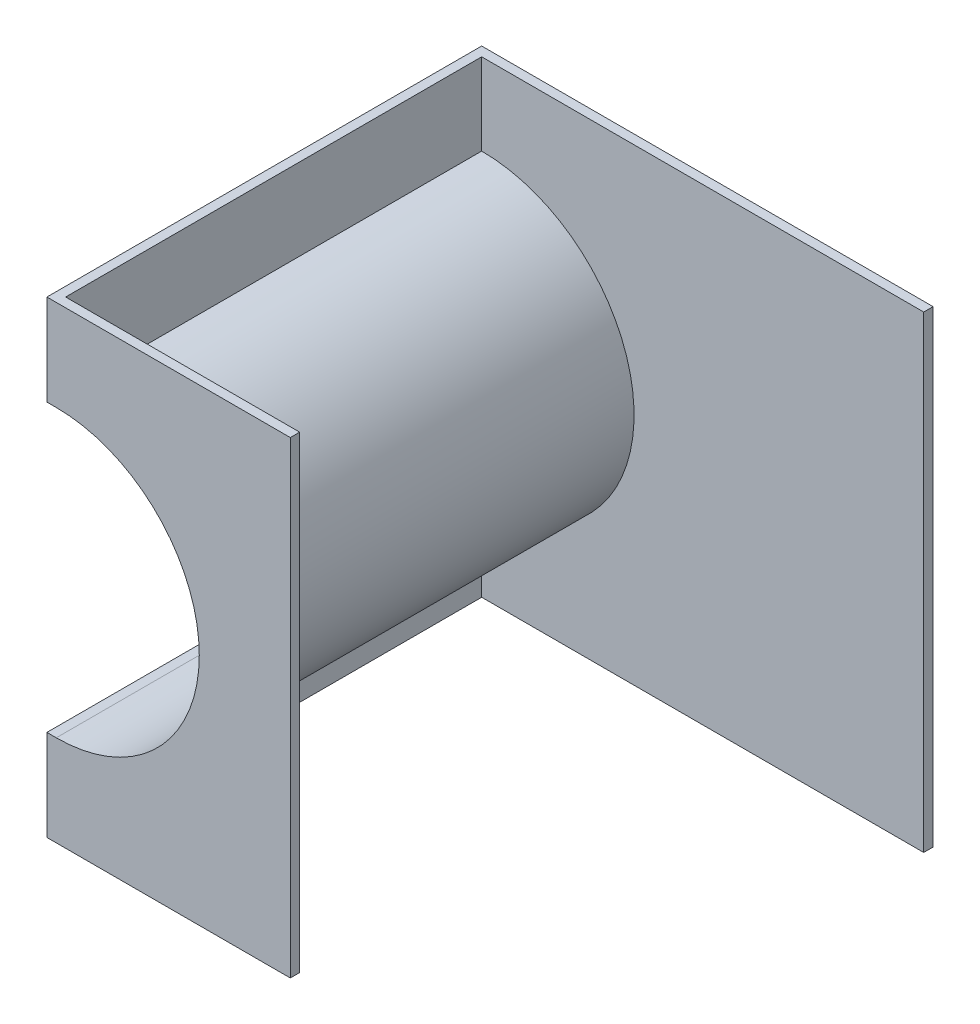
SolidWorks part; units mm, degrees
ref_plane "Přední rovina" through (0, 0, 0) normal (0, 0, 1) x (1, 0, 0)
ref_plane "Horní rovina" through (0, 0, 0) normal (0, 1, 0) x (1, 0, 0)
ref_plane "Pravá rovina" through (0, 0, 0) normal (1, 0, 0) x (0, 0, -1)
sketch "Skica1" plane through (0, 0, 0) normal (0, 0, 1) x (1, 0, 0)
  line L6 (0, 0) -> (0, 0.293) construction
  line L7 (0, 0) -> (0, -0.293) construction
  line L8 (0, 0.275) -> (-0.018, 0.275)
  line L9 (-0.018, 0.275) -> (-0.018, 0.45)
  line L10 (-0.018, 0.45) -> (0, 0.45)
  line L11 (0, 0.45) -> (0, 0.293)
  line L12 (0, -0.275) -> (-0.018, -0.275)
  line L13 (-0.018, -0.275) -> (-0.018, -0.45)
  line L14 (-0.018, -0.45) -> (0, -0.45)
  line L15 (0, -0.45) -> (0, -0.293)
  line L16 (0.275, 0) -> (0.293, 0) construction
  arc A2 (0, -0.293) -> (0, 0.293) centre (0, 0) ccw
  arc A3 (0, 0.275) -> (0, -0.275) centre (0, 0) cw
  dimension "D4" = 0.293
  dimension "D2" = 0.018
  dimension "D3" = 0.9
  dimension "D1" = 0.55
extrude "Přidat vysunutím1" add sketch "Skica1" along normal mid plane 0.8
sketch "Skica2" plane through (0, 0, 0.4) normal (0, 0, 1) x (1, 0, 0)
  line L11 (0, 0.45) -> (0.45, 0.45)
  line L12 (0.45, 0.45) -> (0.45, -0.45)
  line L13 (0.45, -0.45) -> (0, -0.45)
  line L19 (0, 0.45) -> (-0.018, 0.45)
  line L20 (-0.018, 0.45) -> (-0.018, 0.275)
  line L21 (-0.018, 0.275) -> (0, 0.275)
  line L22 (0, -0.275) -> (-0.018, -0.275)
  line L23 (-0.018, -0.275) -> (-0.018, -0.45)
  line L24 (-0.018, -0.45) -> (0, -0.45)
  line L25 (0, -0.45) -> (0, -0.293)
  line L26 (0, 0.293) -> (0, 0.45)
  line L27 (0, 0.45) -> (-0.018, 0.45)
  line L28 (-0.018, 0.45) -> (-0.018, 0.275)
  line L29 (-0.018, 0.275) -> (0, 0.275)
  line L30 (0, -0.275) -> (-0.018, -0.275)
  line L31 (-0.018, -0.275) -> (-0.018, -0.45)
  line L32 (-0.018, -0.45) -> (0, -0.45)
  line L33 (0, -0.45) -> (0, -0.293) construction
  line L34 (0, 0.293) -> (0, 0.45) construction
  arc A4 (0, -0.275) -> (0, 0.275) centre (0, 0) ccw
  arc A5 (0, -0.293) -> (0, 0.293) centre (0, 0) ccw
  arc A6 (0, -0.275) -> (0, 0.275) centre (0, 0) ccw
  arc A7 (0, -0.293) -> (0, 0.293) centre (0, 0) ccw construction
  dimension "D1" = 0
  dimension "D2" = 0.45
extrude "Přidat vysunutím2" add sketch "Skica2" along normal blind 0.018
sketch "Skica3" plane through (0, 0, -0.4) normal (0, 0, -1) x (-1, 0, 0)
  line L3 (0, 0.45) -> (-0.85, 0.45)
  line L4 (-0.85, 0.45) -> (-0.85, -0.45)
  line L5 (-0.85, -0.45) -> (0, -0.45)
  line L20 (0.018, 0.45) -> (0, 0.45)
  line L21 (0, 0.45) -> (0, 0.293)
  line L22 (0, -0.293) -> (0, -0.45)
  line L23 (0, -0.45) -> (0.018, -0.45)
  line L25 (0.018, -0.45) -> (0.018, -0.275)
  line L27 (0.018, -0.275) -> (0, -0.275)
  line L29 (0, 0.275) -> (0.018, 0.275)
  line L31 (0.018, 0.275) -> (0.018, 0.45)
  line L33 (0.018, 0.45) -> (0, 0.45)
  line L34 (0, 0.45) -> (0, 0.293) construction
  line L35 (0, -0.293) -> (0, -0.45) construction
  line L36 (0, -0.45) -> (0.018, -0.45)
  line L37 (0.018, -0.45) -> (0.018, -0.275)
  line L38 (0.018, -0.275) -> (0, -0.275)
  line L39 (0, 0.275) -> (0.018, 0.275)
  line L40 (0.018, 0.275) -> (0.018, 0.45)
  arc A2 (0, 0.293) -> (0, -0.293) centre (0, 0) ccw
  arc A6 (0, 0.275) -> (0, -0.275) centre (0, 0) ccw
  arc A8 (0, 0.293) -> (0, -0.293) centre (0, 0) ccw construction
  arc A9 (0, 0.275) -> (0, -0.275) centre (0, 0) ccw
  dimension "D2" = 0.85
  dimension "D1" = 0
extrude "Přidat vysunutím3" add sketch "Skica3" along normal blind 0.018
equation "\"thickness\"=0.018"
equation "\"D2@Skica1\"=\"thickness\""
equation "\"D1@Přidat vysunutím2\"=\"thickness\""
equation "\"D1@Přidat vysunutím3\"=\"thickness\""
